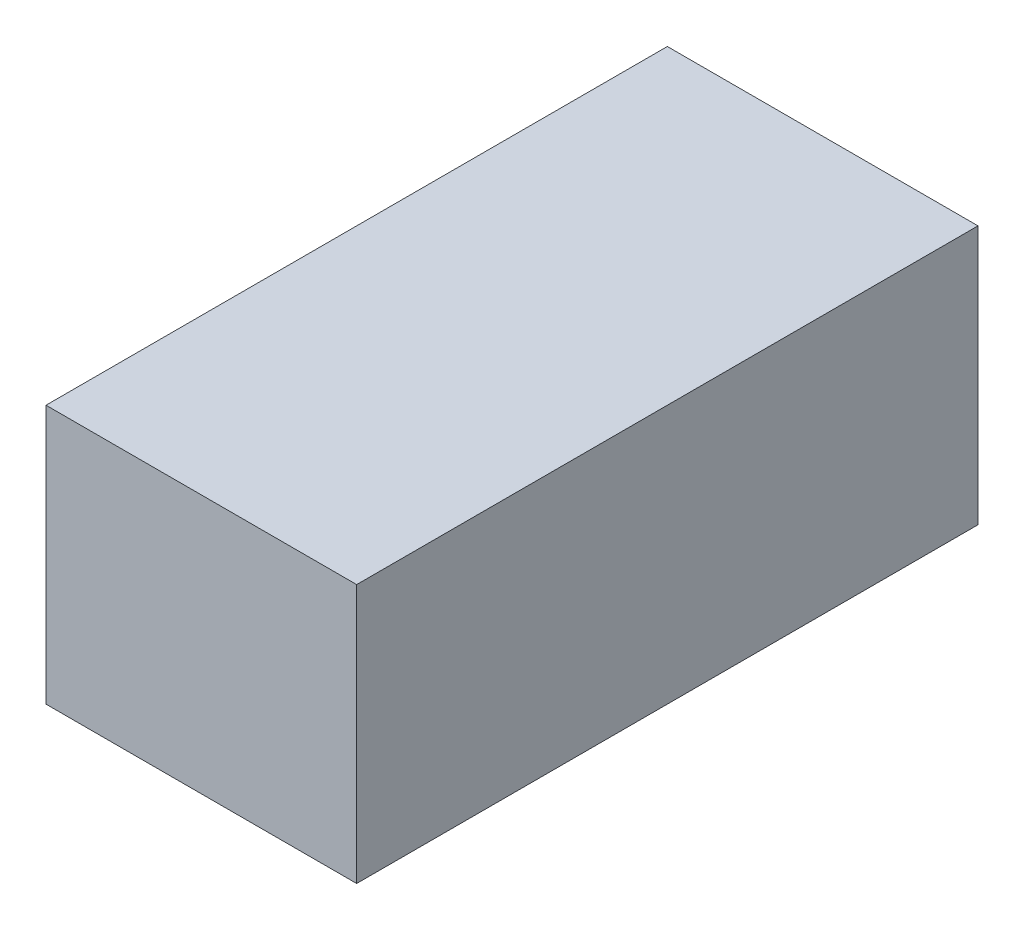
SolidWorks part; units mm, degrees
material "Polyethylene Cross-Linked"
ref_plane "Front Plane" through (0, 0, 0) normal (0, 0, 1) x (1, 0, 0)
ref_plane "Top Plane" through (0, 0, 0) normal (0, 1, 0) x (1, 0, 0)
ref_plane "Right Plane" through (0, 0, 0) normal (1, 0, 0) x (0, 0, -1)
sketch "Sketch1" plane through (0, 0, 0) normal (0, 1, 0) x (1, 0, 0)
  line L1 (-152.4, 304.8) -> (152.4, 304.8)
  line L2 (-152.4, 304.8) -> (-152.4, -304.8)
  line L3 (-152.4, -304.8) -> (152.4, -304.8)
  line L4 (152.4, 304.8) -> (152.4, -304.8)
  line L5 (-152.4, 304.8) -> (152.4, -304.8) construction
  line L6 (-152.4, -304.8) -> (152.4, 304.8) construction
  point P0 (0, 0)
  dimension "D1" = 304.8
  dimension "D2" = 609.6
extrude "Boss-Extrude1" add sketch "Sketch1" along normal blind 254
